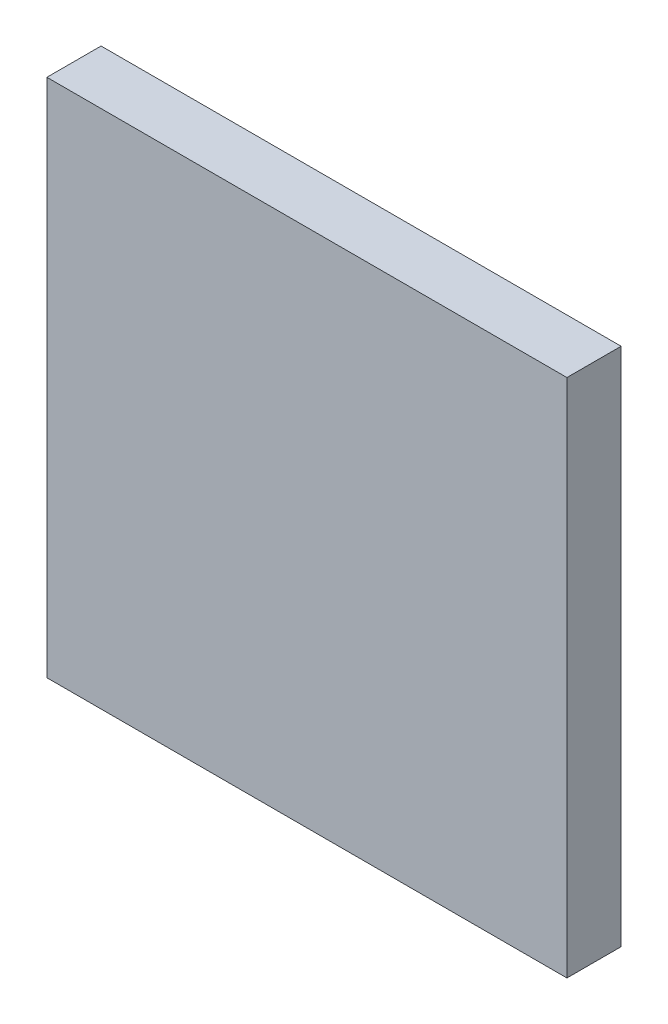
SolidWorks part; units mm, degrees
ref_plane "Front Plane" through (0, 0, 0) normal (0, 0, 1) x (1, 0, 0)
ref_plane "Top Plane" through (0, 0, 0) normal (0, 1, 0) x (1, 0, 0)
ref_plane "Right Plane" through (0, 0, 0) normal (1, 0, 0) x (0, 0, -1)
sketch "Sketch1" plane through (0, 0, 0) normal (0, 0, 1) x (1, 0, 0)
  line L1 (-48, 48) -> (48, 48)
  line L2 (-48, 48) -> (-48, -48)
  line L3 (-48, -48) -> (48, -48)
  line L4 (48, 48) -> (48, -48)
  line L5 (-48, 48) -> (48, -48) construction
  line L6 (-48, -48) -> (48, 48) construction
  point P0 (0, 0)
  dimension "D1" = 96
  dimension "D2" = 96
extrude "Boss-Extrude1" add sketch "Sketch1" along normal mid plane 10
